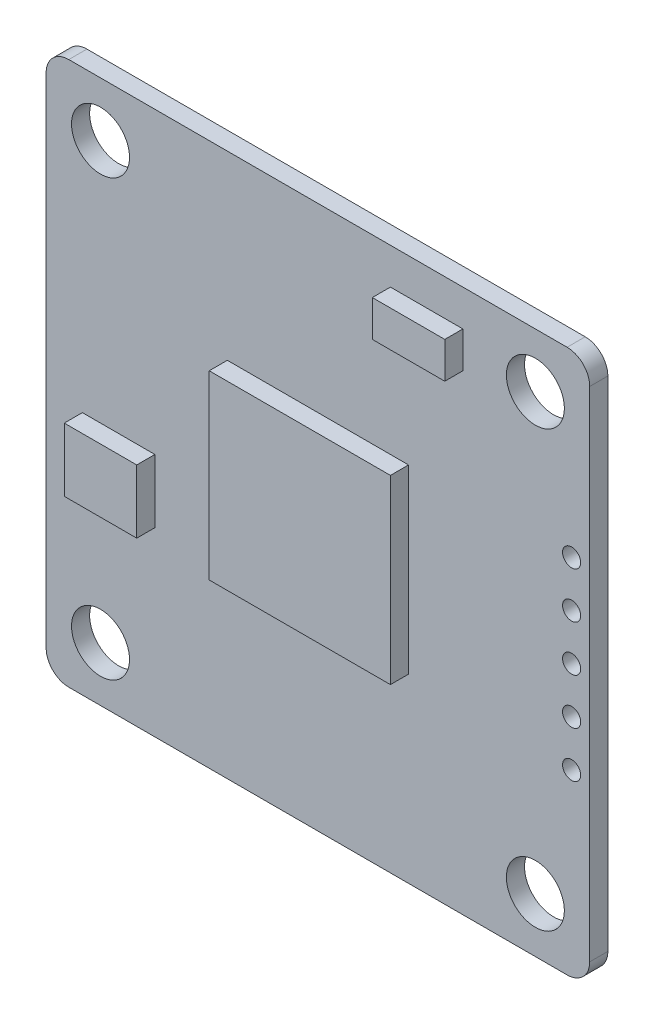
SolidWorks part; units mm, degrees
ref_plane "正面" through (0, 0, 0) normal (0, 0, 1) x (1, 0, 0)
ref_plane "平面" through (0, 0, 0) normal (0, 1, 0) x (1, 0, 0)
ref_plane "右側面" through (0, 0, 0) normal (1, 0, 0) x (0, 0, -1)
sketch "ｽｹｯﾁ1" plane through (0, 0, 0) normal (0, 0, 1) x (1, 0, 0)
  line L1 (-15, 15) -> (15, 15)
  line L2 (-15, 15) -> (-15, -15)
  line L3 (-15, -15) -> (15, -15)
  line L4 (15, 15) -> (15, -15)
  line L5 (-15, 15) -> (15, -15) construction
  line L6 (-15, -15) -> (15, 15) construction
  point P0 (0, 0)
  dimension "D1" = 30
  dimension "D2" = 30
extrude "ﾎﾞｽ - 押し出し1" add sketch "ｽｹｯﾁ1" along normal blind 1
fillet "ﾌｨﾚｯﾄ1" radius 1.25 4 edges at (-15, 15, 0.5) (-15, -15, 0.5) (15, -15, 0.5) (15, 15, 0.5)
sketch "ｽｹｯﾁ2" plane through (0, 0, 1) normal (0, 0, 1) x (1, 0, 0)
  line L0 (13.75, 15) -> (-13.75, 15) construction
  line L1 (-15, 13.75) -> (-15, -13.75) construction
  line L2 (-13.75, -15) -> (13.75, -15) construction
  line L3 (15, -13.75) -> (15, 13.75) construction
  circle A0 centre (-12, 12) radius 1.6
  circle A1 centre (12, 12) radius 1.6
  circle A2 centre (-12, -12) radius 1.6
  circle A3 centre (12, -12) radius 1.6
  dimension "D1" = 3
  dimension "D3" = 3.2
  dimension "D4" = 3
  dimension "D5" = 3
  dimension "D6" = 3.2
  dimension "D7" = 3
  dimension "D8" = 3
  dimension "D9" = 3
  dimension "D10" = 3
  dimension "D11" = 3.2
  dimension "D12" = 3.2
  dimension "D2" = 3
extrude "ｶｯﾄ - 押し出し1" cut sketch "ｽｹｯﾁ2" against normal blind 1
sketch "ｽｹｯﾁ3" plane through (0, 0, 1) normal (0, 0, 1) x (1, 0, 0)
  line L0 (15, -13.75) -> (15, 13.75) construction
  circle A0 centre (14, 0) radius 0.5
  point P4 (15, 0)
  dimension "D1" = 1
  dimension "D2" = 1
  dimension "D3" = 0
extrude "ｶｯﾄ - 押し出し2" cut sketch "ｽｹｯﾁ3" against normal blind 1
pattern_linear "直線ﾊﾟﾀｰﾝ1" count 3 spacing 2.54 along (0, -1, 0) count 3 spacing 2.54 along (0, 1, 0) of "ｶｯﾄ - 押し出し2"
sketch "ｽｹｯﾁ4" plane through (0, 0, 1) normal (0, 0, 1) x (1, 0, 0)
  line L1 (-5, 5) -> (5, 5)
  line L2 (-5, 5) -> (-5, -5)
  line L3 (-5, -5) -> (5, -5)
  line L4 (5, 5) -> (5, -5)
  line L5 (-5, 5) -> (5, -5) construction
  line L6 (-5, -5) -> (5, 5) construction
  point P0 (0, 0)
  dimension "D1" = 10
  dimension "D2" = 10
extrude "ﾎﾞｽ - 押し出し2" add sketch "ｽｹｯﾁ4" along normal blind 1
sketch "ｽｹｯﾁ5" plane through (0, 0, 1) normal (0, 0, 1) x (1, 0, 0)
  line L0 (-15, 13.75) -> (-15, -13.75) construction
  line L1 (-13, -1.5) -> (-9, -1.5)
  line L2 (-13, -1.5) -> (-13, -5)
  line L3 (-13, -5) -> (-9, -5)
  line L4 (-9, -1.5) -> (-9, -5)
  line L5 (4, 13) -> (8, 13)
  line L6 (4, 13) -> (4, 11)
  line L7 (4, 11) -> (8, 11)
  line L8 (8, 13) -> (8, 11)
  line L9 (-13.75, -15) -> (13.75, -15) construction
  line L10 (13.75, 15) -> (-13.75, 15) construction
  line L11 (15, -13.75) -> (15, 13.75) construction
  dimension "D1" = 4
  dimension "D2" = 3.5
  dimension "D3" = 2
  dimension "D4" = 10
  dimension "D5" = 2
  dimension "D6" = 4
  dimension "D7" = 2
  dimension "D8" = 7
extrude "ﾎﾞｽ - 押し出し3" add sketch "ｽｹｯﾁ5" along normal blind 1
